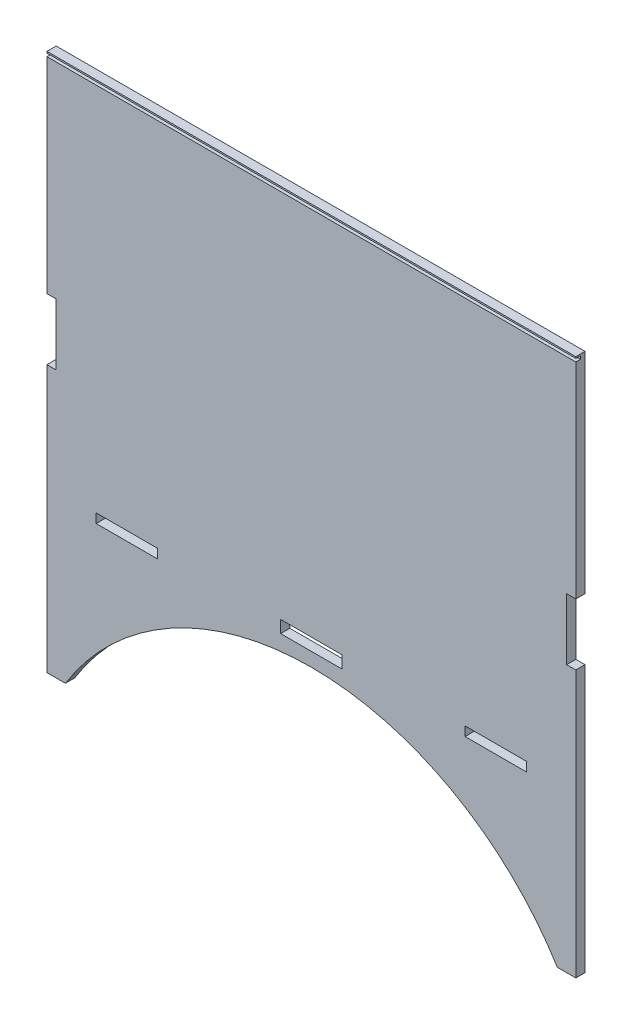
SolidWorks part; units mm, degrees
ref_plane "Plan de face" through (0, 0, 0) normal (0, 0, 1) x (1, 0, 0)
ref_plane "Plan de dessus" through (0, 0, 0) normal (0, 1, 0) x (1, 0, 0)
ref_plane "Plan de droite" through (0, 0, 0) normal (1, 0, 0) x (0, 0, -1)
sketch "Esquisse1" plane through (0, 0, 0) normal (0, 0, 1) x (1, 0, 0)
  line L0 (-109.4992, 0) -> (62.5008, 0)
  line L1 (62.5008, 0) -> (62.5008, -175)
  line L3 (-109.4992, -175) -> (-109.4992, 0)
  line L5 (-109.4992, -175) -> (-103.4992, -175)
  line L6 (56.5008, -175) -> (62.5008, -175)
  line L8 (-93.4992, -122) -> (-73.4992, -122)
  line L9 (-93.4992, -122) -> (-93.4992, -125)
  line L10 (-93.4992, -125) -> (-73.4992, -125)
  line L11 (-73.4992, -122) -> (-73.4992, -125)
  line L12 (-33.4992, -122) -> (-13.4992, -122)
  line L13 (-33.4992, -122) -> (-33.4992, -126)
  line L14 (-33.4992, -126) -> (-13.4992, -126)
  line L15 (-13.4992, -122) -> (-13.4992, -126)
  line L16 (26.5008, -122) -> (46.5008, -122)
  line L17 (26.5008, -122) -> (26.5008, -125)
  line L18 (26.5008, -125) -> (46.5008, -125)
  line L19 (46.5008, -122) -> (46.5008, -125)
  arc A0 (-103.4992, -175) -> (56.5008, -175) centre (-23.4992, -224.6279) cw
  point P12 (-106.4992, -175)
  dimension "D4" = 50
  dimension "D1" = 172
  dimension "D2" = 175
  dimension "D3" = 172
  dimension "D5" = 6
  dimension "D6" = 20
  dimension "D7" = 16
  dimension "D8" = 3
  dimension "D9" = 40
  dimension "D10" = 40
  dimension "D11" = 4
extrude "Boss.-Extru.1" add sketch "Esquisse1" along normal blind 3
sketch "Esquisse2" plane through (0, 0, 3) normal (0, 0, 1) x (1, 0, 0)
  line L20 (-109.4992, 0) -> (-109.4992, -1.5) construction
  line L21 (-109.4992, 0) -> (-109.4992, -175) construction
  line L22 (-109.4992, -1.5) -> (-109.4992, -0.5) construction
  line L23 (-109.4992, -1.5) -> (-109.4992, -0.5)
  line L24 (-109.4992, -1.5) -> (62.5008, -1.5)
  line L25 (-109.4992, -0.5) -> (62.5008, -0.5)
  line L26 (62.5008, -1.5) -> (62.5008, -0.5)
  line L27 (62.5008, -175) -> (62.5008, 0) construction
  line L28 (62.5008, 0) -> (-109.4992, 0) construction
  dimension "D1" = 0.5
  dimension "D2" = 1
extrude "Enlèv. mat.-Extru.1" cut sketch "Esquisse2" against normal blind 1.5
sketch "Esquisse4" plane through (0, 0, 3) normal (0, 0, 1) x (1, 0, 0)
  line L0 (-109.4992, -88.25) -> (-109.4992, -68.25) construction
  line L1 (-109.4992, -1.5) -> (-109.4992, -175) construction
  line L2 (-109.4992, -88.25) -> (-109.4992, -68.25)
  line L3 (-109.4992, -88.25) -> (-106.4992, -88.25)
  line L4 (-109.4992, -68.25) -> (-106.4992, -68.25)
  line L5 (-106.4992, -88.25) -> (-106.4992, -68.25)
  line L7 (62.5008, -88.25) -> (62.5008, -68.25)
  line L8 (62.5008, -175) -> (62.5008, -1.5) construction
  line L9 (62.5008, -88.25) -> (62.5008, -68.25) construction
  line L10 (62.5008, -88.25) -> (59.5008, -88.25)
  line L11 (62.5008, -68.25) -> (59.5008, -68.25)
  line L12 (59.5008, -88.25) -> (59.5008, -68.25)
  dimension "D1" = 3
  dimension "D2" = 20
extrude "Enlèv. mat.-Extru.2" cut sketch "Esquisse4" against normal through all
